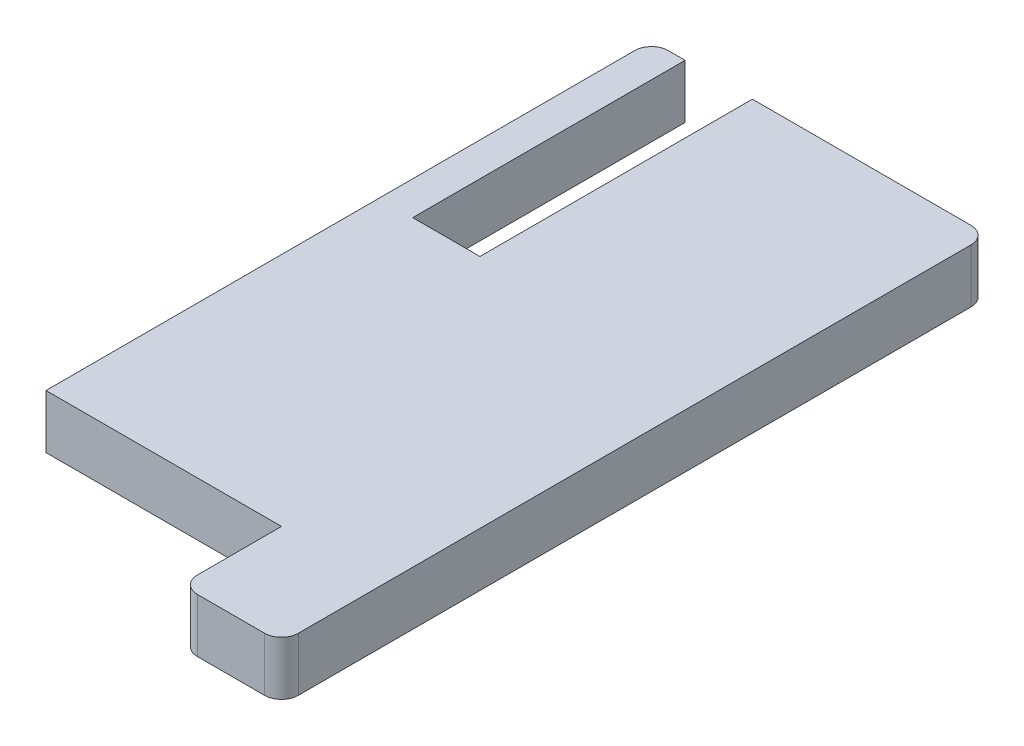
SolidWorks part; units mm, degrees
ref_plane "Front Plane" through (0, 0, 0) normal (0, 0, 1) x (1, 0, 0)
ref_plane "Top Plane" through (0, 0, 0) normal (0, 1, 0) x (1, 0, 0)
ref_plane "Right Plane" through (0, 0, 0) normal (1, 0, 0) x (0, 0, -1)
sketch "Sketch1" plane through (0, 0, 0) normal (0, 1, 0) x (1, 0, 0)
  line L0 (623.012, -61.4484) -> (625.012, -61.4484)
  line L2 (615.512, -58.4484) -> (616.262, -58.4484)
  line L3 (618.762, -58.4484) -> (622.512, -58.4484)
  line L5 (615.512, -58.4484) -> (615.512, -40.9484)
  line L6 (616.012, -40.4484) -> (616.262, -40.4484)
  line L7 (618.762, -40.4484) -> (625.012, -40.4484)
  line L8 (625.512, -60.9484) -> (625.512, -40.9484)
  line L10 (622.512, -60.9484) -> (622.512, -58.4484)
  line L37 (616.512, -48.5484) -> (618.512, -48.5484)
  line L38 (616.262, -58.4484) -> (618.762, -58.4484)
  line L40 (618.512, -48.5484) -> (618.512, -40.4484)
  line L42 (616.512, -48.5484) -> (616.512, -40.4484)
  line L43 (616.512, -40.4484) -> (616.262, -40.4484)
  line L44 (618.762, -40.4484) -> (618.512, -40.4484)
  arc A0 (616.012, -40.4484) -> (615.512, -40.9484) centre (616.012, -40.9484) ccw
  arc A1 (625.012, -61.4484) -> (625.512, -60.9484) centre (625.012, -60.9484) ccw
  arc A2 (625.512, -40.9484) -> (625.012, -40.4484) centre (625.012, -40.9484) ccw
  arc A3 (622.512, -60.9484) -> (623.012, -61.4484) centre (623.012, -60.9484) ccw
extrude "Boss-Extrude1" add sketch "Sketch1" along normal blind 1.6
